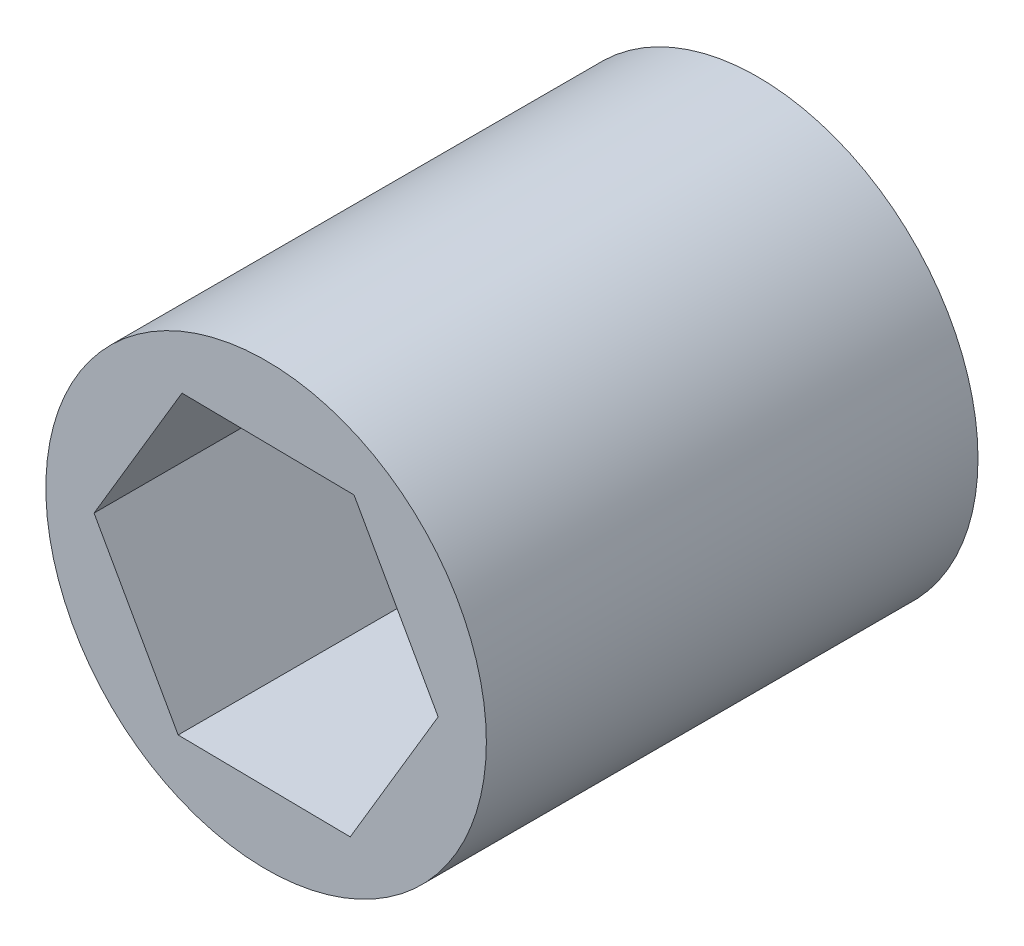
SolidWorks part; units mm, degrees
ref_plane "Front Plane" through (0, 0, 0) normal (0, 0, 1) x (1, 0, 0)
ref_plane "Top Plane" through (0, 0, 0) normal (0, 1, 0) x (1, 0, 0)
ref_plane "Right Plane" through (0, 0, 0) normal (1, 0, 0) x (0, 0, -1)
sketch "Sketch1" plane through (0, 0, 0) normal (0, 0, 1) x (1, 0, 0)
  line L1 (-3.4217, 6.1067) -> (-6.9994, 0.09)
  line L2 (-6.9994, 0.09) -> (-3.5777, -6.0167)
  line L3 (-3.5777, -6.0167) -> (3.4217, -6.1067)
  line L4 (3.4217, -6.1067) -> (6.9994, -0.09)
  line L5 (6.9994, -0.09) -> (3.5777, 6.0167)
  line L6 (3.5777, 6.0167) -> (-3.4217, 6.1067)
  circle A0 centre (0, 0) radius 6.0622 construction
  circle A1 centre (0, 0) radius 8.9605
  dimension "D1" = 7
extrude "Boss-Extrude1" add sketch "Sketch1" along normal blind 20
